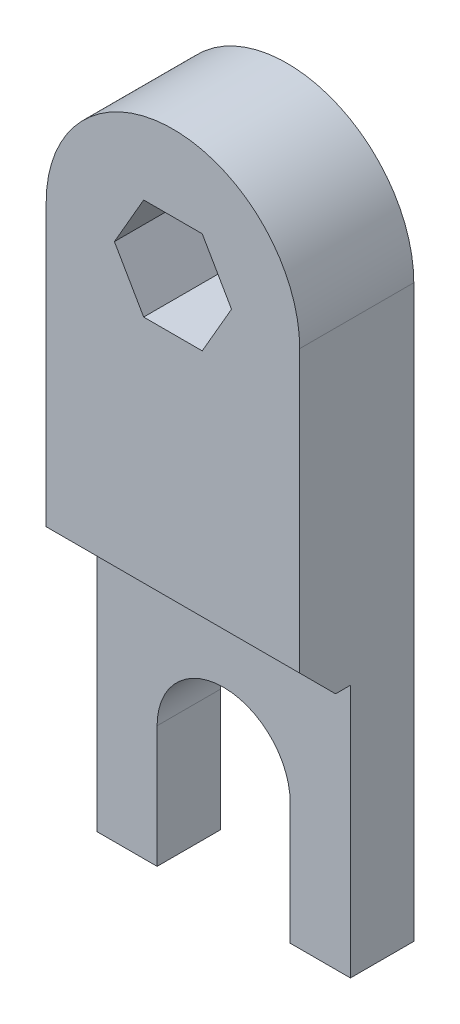
SolidWorks part; units mm, degrees
ref_plane "Front Plane" through (0, 0, 0) normal (0, 0, 1) x (1, 0, 0)
ref_plane "Top Plane" through (0, 0, 0) normal (0, 1, 0) x (1, 0, 0)
ref_plane "Right Plane" through (0, 0, 0) normal (1, 0, 0) x (0, 0, -1)
ref_plane "Plane1" through (0, 0, 0) normal (0, 0, -1) x (-1, 0, 0)
sketch "Sketch1" plane through (0, 0, 0) normal (0, 0, -1) x (-1, 0, 0)
  line L0 (-4, 14) -> (-4, 4)
  line L1 (-4, 4) -> (4, 4)
  line L2 (4, 4) -> (4, 14)
  line L19 (-0.9238, 12.4) -> (-1.8475, 14)
  line L20 (-1.8475, 14) -> (-0.9238, 15.6)
  line L21 (-0.9238, 15.6) -> (0.9238, 15.6)
  line L22 (0.9238, 15.6) -> (1.8475, 14)
  line L23 (1.8475, 14) -> (0.9238, 12.4)
  line L24 (0.9238, 12.4) -> (-0.9238, 12.4)
  arc A0 (4, 14) -> (-4, 14) centre (0, 14) ccw
extrude "Boss-Extrude1" add sketch "Sketch1" against normal blind 3.6
chamfer "Chamfer1" distance 1.1314 angle 45 1 edges at (0, 4, 3.6)
sketch "Sketch6" plane through (0, 0, 0) normal (0, 0, -1) x (-1, 0, 0)
  line L0 (-4, -4) -> (-2.1, -4)
  line L1 (-2.1, -4) -> (-2.1, -0.1564)
  line L8 (2.1, -0.1564) -> (2.1, -4)
  line L9 (2.1, -4) -> (4, -4)
  line L10 (4, -4) -> (4, 4)
  line L11 (4, 4) -> (-4, 4)
  line L12 (-4, 4) -> (-4, -4)
  arc A0 (2.1, -0.1564) -> (-2.1, -0.1564) centre (0, -0.1564) ccw
extrude "Boss-Extrude2" add sketch "Sketch6" against normal blind 2
